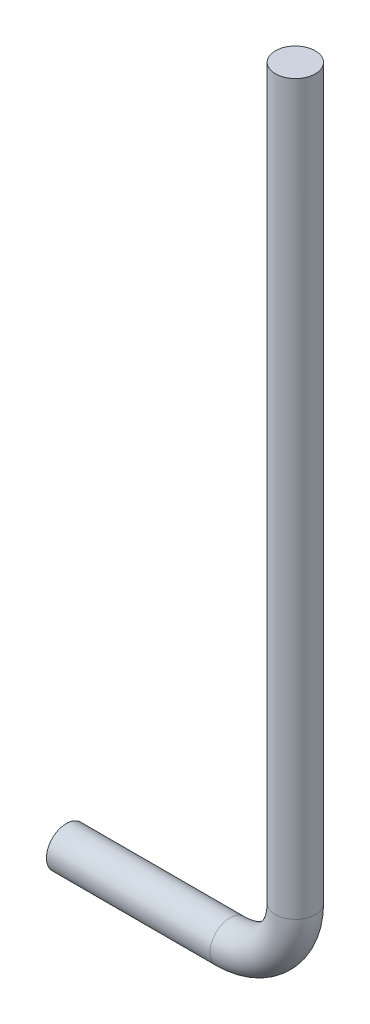
SolidWorks part; units mm, degrees
material "Copper"
ref_plane "Front Plane" through (0, 0, 0) normal (0, 0, 1) x (1, 0, 0)
ref_plane "Top Plane" through (0, 0, 0) normal (0, 1, 0) x (1, 0, 0)
ref_plane "Right Plane" through (0, 0, 0) normal (1, 0, 0) x (0, 0, -1)
ref_plane "Plane1" through (0, 0, -5) normal (0, 0, 1) x (1, 0, 0)
sketch "Sketch1" plane through (0, 0, -5) normal (0, 0, 1) x (1, 0, 0)
  line L0 (35, 91) -> (35, -13)
  line L1 (25, -23) -> (0, -23)
  arc A0 (35, -13) -> (25, -23) centre (25, -13) cw
  dimension "D1" = 10
  dimension "D2" = 35
  dimension "D3" = 35
  dimension "D4" = 23
  dimension "D5" = 104
sketch "Sketch2" plane through (0, 88.3, 0) normal (0, 1, 0) x (1, 0, 0)
  circle A0 centre (35, 5) radius 3.05
  dimension "D1" = 6.1
sweep "Sweep2" add profiles "Sketch2" path "Sketch1"
sketch "Sketch3" plane through (0, 88.3, 0) normal (0, 1, 0) x (1, 0, 0)
  circle A1 centre (35, 5) radius 3.05
  circle A2 centre (35, 5) radius 3.05
  dimension "D1" = 0
extrude "Boss-Extrude1" add sketch "Sketch3" along normal blind 10
